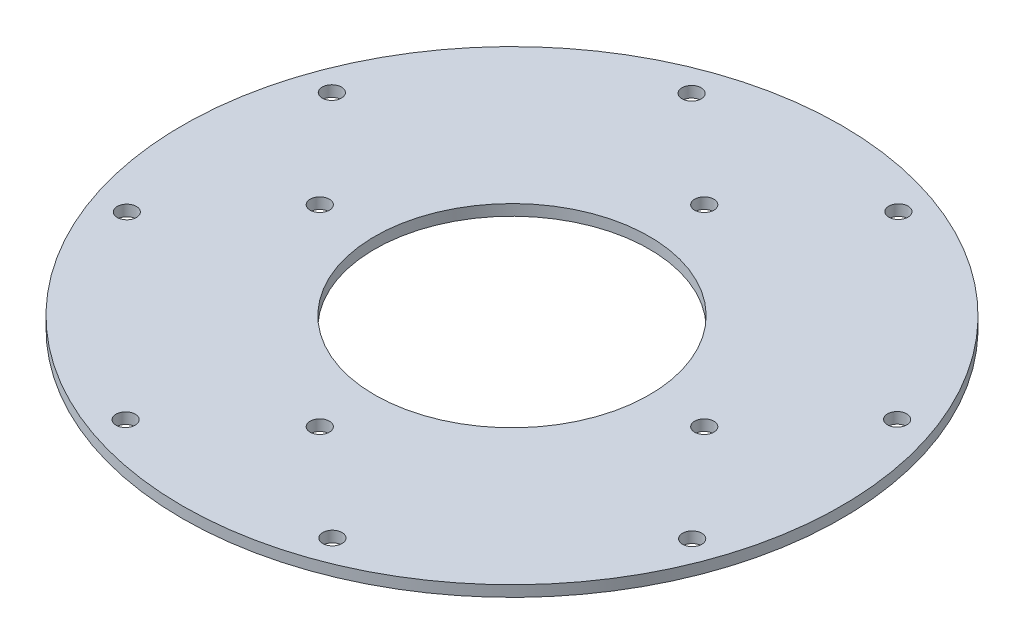
SolidWorks part; units mm, degrees
ref_plane "Ön Düzlem" through (0, 0, 0) normal (0, 0, 1) x (1, 0, 0)
ref_plane "Üst Düzlem" through (0, 0, 0) normal (0, 1, 0) x (1, 0, 0)
ref_plane "Sağ Düzlem" through (0, 0, 0) normal (1, 0, 0) x (0, 0, -1)
sketch "Çizim1" plane through (0, 0, 0) normal (0, 1, 0) x (1, 0, 0)
  circle A0 centre (0, 0) radius 60
  circle A3 centre (-51.5761, 18.7721) radius 1.75
  circle A4 centre (-18.7123, 51.4118) radius 1.75
  circle A5 centre (18.7721, 51.5761) radius 1.75
  circle A6 centre (51.4118, 18.7123) radius 1.75
  circle A7 centre (51.5761, -18.7721) radius 1.75
  circle A8 centre (18.7123, -51.4118) radius 1.75
  circle A9 centre (-18.7721, -51.5761) radius 1.75
  circle A10 centre (-51.4118, -18.7123) radius 1.75
  point P3 (0, 0)
  dimension "D1" = 4
extrude "Yükseklik-Ekstrüzyon1" add sketch "Çizim1" along normal blind 2
sketch "Çizim2" plane through (0, 2, 0) normal (0, 1, 0) x (1, 0, 0)
  circle A2 centre (0, 35) radius 1.75
  circle A3 centre (35, 0) radius 1.75
  circle A4 centre (0, -35) radius 1.75
  circle A5 centre (-35, 0) radius 1.75
  dimension "D1" = 70
  dimension "D3" = 4
extrude "Kes-Ekstrüzyon1" cut sketch "Çizim2" against normal blind 10
sketch "Çizim3" plane through (0, 2, 0) normal (0, 1, 0) x (1, 0, 0)
  circle A0 centre (0, 0) radius 25
extrude "Kes-Ekstrüzyon2" cut sketch "Çizim3" against normal blind 10
